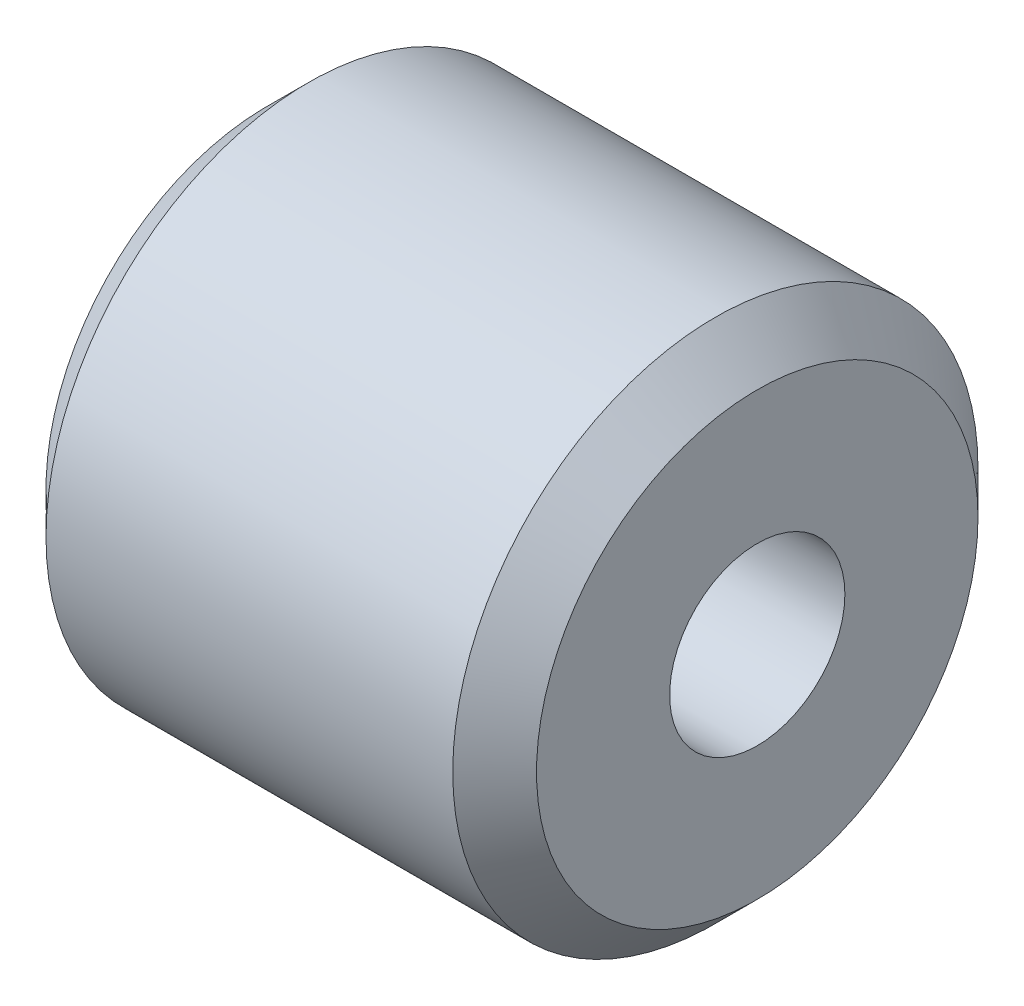
SolidWorks part; units mm, degrees
ref_plane "Front Plane" through (0, 0, 0) normal (0, 0, 1) x (1, 0, 0)
ref_plane "Top Plane" through (0, 0, 0) normal (0, 1, 0) x (1, 0, 0)
ref_plane "Right Plane" through (0, 0, 0) normal (1, 0, 0) x (0, 0, -1)
sketch "Sketch1" plane through (0, 0, 0) normal (1, 0, 0) x (0, 0, -1)
  circle A0 centre (0, 0) radius 1.59
  circle A1 centre (0, 0) radius 4.765
  dimension "D1" = 9.53
  dimension "D2" = 3.18
extrude "Boss-Extrude1" add sketch "Sketch1" along normal mid plane 8.9
chamfer "Chamfer1" distance 0.76 angle 45 2 edges at (-4.45, 0, -4.765) (4.45, 0, -4.765)
